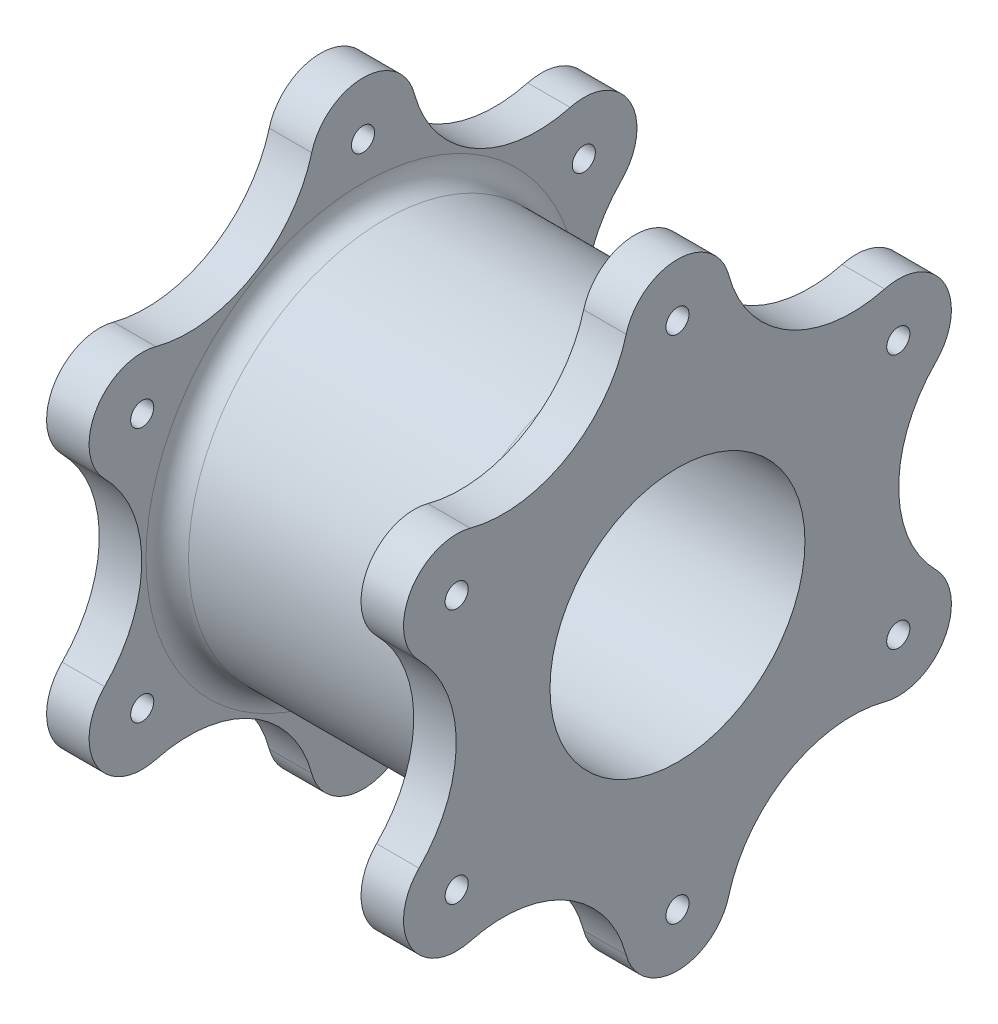
SolidWorks part; units mm, degrees
ref_plane "Front Plane" through (0, 0, 0) normal (0, 0, 1) x (1, 0, 0)
ref_plane "Top Plane" through (0, 0, 0) normal (0, 1, 0) x (1, 0, 0)
ref_plane "Right Plane" through (0, 0, 0) normal (1, 0, 0) x (0, 0, -1)
sketch "Sketch1" plane through (0, 0, 0) normal (1, 0, 0) x (0, 0, -1)
  circle A0 centre (0, 0) radius 38.1 construction
  circle A1 centre (0, 38.1) radius 1.7272
  circle A2 centre (32.9956, 19.05) radius 1.7272
  circle A3 centre (32.9956, -19.05) radius 1.7272
  circle A4 centre (0, -38.1) radius 1.7272
  circle A5 centre (-32.9956, -19.05) radius 1.7272
  circle A6 centre (-32.9956, 19.05) radius 1.7272
  circle A7 centre (0, 0) radius 19.05
  arc A8 (7.6635, 40.1676) -> (-7.6635, 40.1676) centre (0, 38.1) ccw
  arc A9 (38.6179, 13.4471) -> (30.9545, 26.7206) centre (32.9956, 19.05) ccw
  arc A10 (30.9545, -26.7206) -> (38.6179, -13.4471) centre (32.9956, -19.05) ccw
  arc A11 (-7.6635, -40.1676) -> (7.6635, -40.1676) centre (0, -38.1) ccw
  arc A12 (-38.6179, -13.4471) -> (-28.3324, -25.4733) centre (-32.9956, -19.05) ccw
  arc A13 (-30.9545, 26.7206) -> (-38.6179, 13.4471) centre (-32.9956, 19.05) ccw
  arc A14 (-7.6635, 40.1676) -> (-30.9545, 26.7206) centre (-26.0558, 45.13) cw
  arc A15 (30.9545, 26.7206) -> (7.6635, 40.1676) centre (26.0558, 45.13) cw
  arc A16 (38.6179, -13.4471) -> (38.6179, 13.4471) centre (52.1116, 0) cw
  arc A17 (7.6635, -40.1676) -> (30.9545, -26.7206) centre (26.0558, -45.13) cw
  arc A18 (-30.9545, -26.7206) -> (-7.6635, -40.1676) centre (-26.0558, -45.13) cw
  arc A19 (-38.6179, 13.4471) -> (-38.6179, -13.4471) centre (-52.1116, 0) cw
  point P17 (0, 0)
  point P31 (0, 0)
  point P48 (0, 0)
  dimension "D1" = 76.2
  dimension "D2" = 3.4544
  dimension "D4" = 38.1
  dimension "D5" = 15.875
  dimension "D7" = 19.05
  dimension "D3" = 6
  dimension "D6" = 6
  dimension "D8" = 6
extrude "Boss-Extrude1" add sketch "Sketch1" along normal blind 6.35
ref_plane "Plane1" through (-7.62, 0, 0) normal (1, 0, 0) x (0, 0, -1)
ref_plane "Plane2" through (-20.32, 0, 0) normal (1, 0, 0) x (0, 0, -1)
sketch "Sketch3" plane through (0, 0, 0) normal (-1, 0, 0) x (0, 0, 1)
  circle A0 centre (0, 0) radius 29.2516
  arc A1 (-30.9545, 26.7206) -> (-7.6635, 40.1676) centre (-26.0558, 45.13) ccw construction
  circle A2 centre (0, 0) radius 19.05 construction
  circle A3 centre (0, 0) radius 19.05
  dimension "D1" = 3.81
extrude "Boss-Extrude2" add sketch "Sketch3" along normal up to surface (20.32 mm away) up to plane "Plane2"
fillet "Fillet1" radius 3.175 1 edges at (0, 0, -29.2516)
mirror "Mirror3" [suppressed] about plane through (-7.62, 0, 0) normal (1, 0, 0)
mirror "Mirror4" about plane through (-20.32, 0, 0) normal (1, 0, 0) of bodies 102
